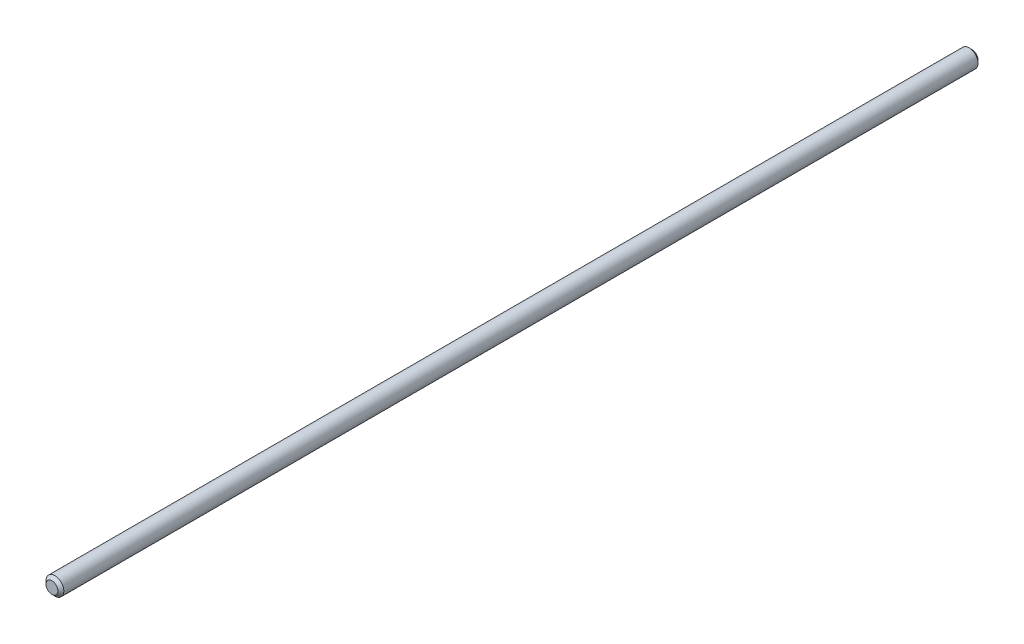
SolidWorks part; units mm, degrees
material "AISI 1020"
ref_plane "Спереди" through (0, 0, 0) normal (0, 0, 1) x (1, 0, 0)
ref_plane "Сверху" through (0, 0, 0) normal (0, 1, 0) x (1, 0, 0)
ref_plane "Справа" through (0, 0, 0) normal (1, 0, 0) x (0, 0, -1)
sketch "Эскиз1" plane through (0, 0, 0) normal (0, 0, 1) x (1, 0, 0)
  circle A0 centre (0, 0) radius 1.5
  dimension "D1" = 3
extrude "Бобышка-Вытянуть1" add sketch "Эскиз1" along normal blind 155
chamfer "Фаска1" distance 0.5 angle 45 2 edges at (1.5, 0, 0) (1.5, 0, 155)
